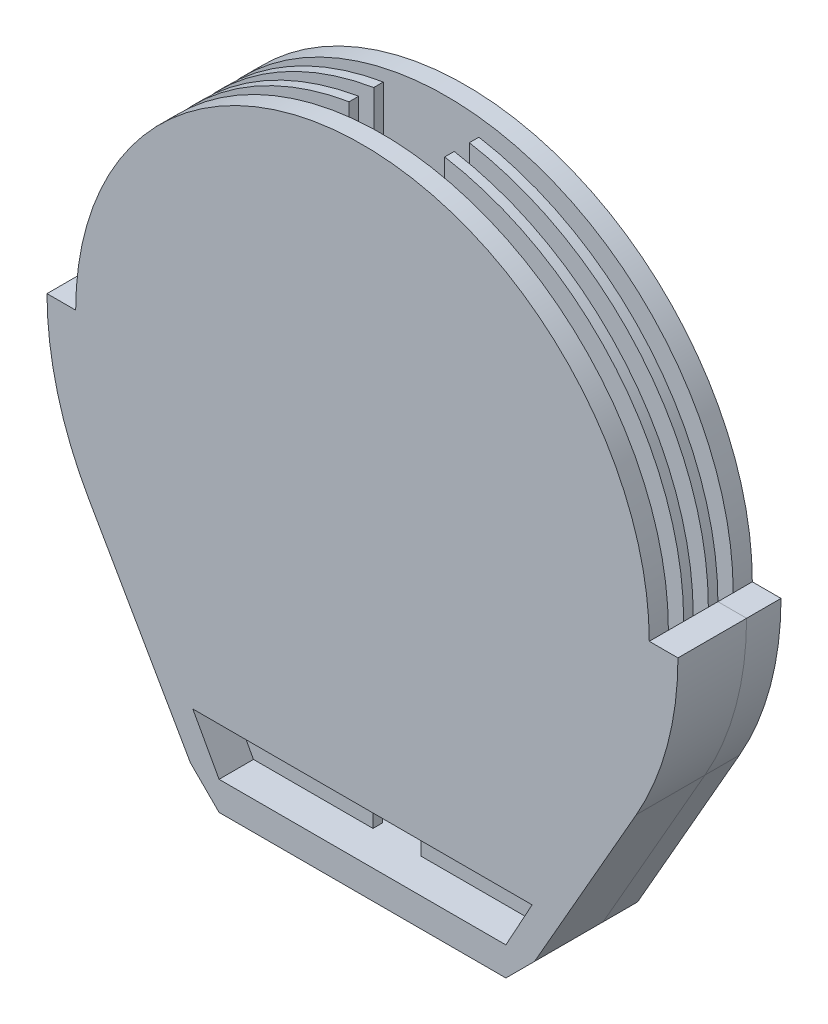
SolidWorks part; units mm, degrees
ref_plane "Plano frontal" through (0, 0, 0) normal (0, 0, 1) x (1, 0, 0)
ref_plane "Plano superior" through (0, 0, 0) normal (0, 1, 0) x (1, 0, 0)
ref_plane "Plano direito" through (0, 0, 0) normal (1, 0, 0) x (0, 0, -1)
sketch "Esboço1" plane through (0, 0, 0) normal (0, 0, 1) x (1, 0, 0)
  line L0 (5, -35) -> (15, -35)
  line L1 (-15, -35) -> (-5, -35)
  line L2 (15, -35) -> (26.2929, -14.4459)
  line L3 (-15, -35) -> (-26.2929, -14.4459)
  line L4 (-12, -30) -> (-5, -30)
  line L5 (-12, -30) -> (-21.889, -12.0777)
  line L6 (12, -30) -> (21.889, -12.0777)
  line L9 (5, -30) -> (12, -30)
  line L10 (-5, -30) -> (-2.5, -30)
  line L11 (-2.5, -32.5) -> (-2.5, -35)
  line L12 (-2.5, -35) -> (-5, -35)
  line L13 (2.5, -32.5) -> (2.5, -35)
  line L14 (2.5, -35) -> (5, -35)
  line L15 (-2.5, -32.5) -> (-2.5, -30)
  line L16 (2.5, -32.5) -> (2.5, -30)
  line L17 (2.5, -30) -> (5, -30)
  arc A0 (26.2929, -14.4459) -> (-26.2929, -14.4459) centre (0, 0) ccw
  arc A1 (21.889, -12.0777) -> (-21.889, -12.0777) centre (0, 0) ccw
  point P5 (0, -30)
  point P8 (0, -35)
  point P13 (0, -30)
  dimension "D1" = 60
  dimension "D2" = 50
  dimension "D8" = 2.5
  dimension "D3" = 30
  dimension "D4" = 24
  dimension "D5" = 10
  dimension "D6" = 5
  dimension "D7" = 5
extrude "Ressalto-extrusão3" add sketch "Esboço1" along normal blind 1
sketch "Esboço2" plane through (0, 0, 1) normal (0, 0, 1) x (1, 0, 0)
  line L0 (-30, 0) -> (-33, 0)
  line L1 (30, 0) -> (33, 0)
  line L2 (-15, -35) -> (-18, -35)
  line L3 (15, -35) -> (18, -35)
  line L4 (-18, -35) -> (-28.6469, -16.3816)
  line L5 (18, -35) -> (28.6469, -16.3816)
  line L6 (-15, -35) -> (-15, -38)
  line L7 (15, -35) -> (15, -38)
  line L8 (-15, -38) -> (15, -38)
  line L9 (18, -35) -> (15, -38)
  line L10 (-18, -35) -> (-15, -38)
  line L11 (-15, -35) -> (-26.2929, -14.4459)
  line L12 (15, -35) -> (26.2929, -14.4459)
  line L13 (-15, -35) -> (15, -35)
  arc A0 (26.2929, -14.4459) -> (-26.2929, -14.4459) centre (0, 0) ccw construction
  arc A1 (-33, 0) -> (-28.6469, -16.3816) centre (0, 0) ccw
  arc A2 (28.6469, -16.3816) -> (33, 0) centre (0, 0) ccw
  arc A3 (26.2929, -14.4459) -> (30, 0) centre (0, 0) ccw
  arc A4 (-30, 0) -> (-26.2929, -14.4459) centre (0, 0) ccw
  line M15 (2.5, -35) -> (15, -35)
  line M16 (15, -35) -> (26.2929, -14.4459)
  arc M17 (26.2929, -14.4459) -> (-26.2929, -14.4459) centre (0, 0) ccw
  line M18 (-26.2929, -14.4459) -> (-15, -35)
  line M19 (-15, -35) -> (-2.5, -35)
  dimension "D1" = 3
  dimension "D3" = 3
  dimension "D4" = 3
  dimension "D5" = 3
  dimension "D6" = 3
extrude "Ressalto-extrusão4" add sketch "Esboço2" against normal blind 3.58 contours L13 L6 L8 L7 M19 M15 | L9 L3 L7 | L5 A2 L1 L3 M17 M16 | L2 L10 L6 | L0 A1 L4 L2 M18 M17
sketch "Esboço4" plane through (0, 0, -2.58) normal (0, 0, -1) x (-1, 0, 0)
  line L0 (-15, -35) -> (-2.5, -35)
  line L1 (15, -35) -> (26.2929, -14.4459)
  line L2 (-15, -35) -> (-26.2929, -14.4459)
  line L3 (-12, -30) -> (-21.889, -12.0777)
  line L4 (12, -30) -> (21.889, -12.0777)
  line L5 (-2.5, -30) -> (-12, -30)
  line L6 (-2.5, -30) -> (-2.5, -35)
  line L7 (2.5, -35) -> (2.5, -30)
  line L8 (2.5, -30) -> (12, -30)
  line L9 (2.5, -35) -> (15, -35)
  arc A0 (26.2929, -14.4459) -> (-26.2929, -14.4459) centre (0, 0) ccw
  arc A1 (21.889, -12.0777) -> (-21.889, -12.0777) centre (0, 0) ccw
extrude "Ressalto-extrusão5" add sketch "Esboço4" against normal blind 1
sketch "Esboço5" plane through (0, 0, 1) normal (0, 0, 1) x (1, 0, 0)
  line L0 (-15, -38) -> (-18, -35)
  line L1 (-18, -35) -> (-28.6469, -16.3816)
  line L2 (-15, -38) -> (15, -38)
  line L3 (15, -38) -> (18, -35)
  line L4 (18, -35) -> (28.6469, -16.3816)
  line L5 (0, -35) -> (12.5, -35)
  line L6 (-12.5, -35) -> (-15, -35)
  line L7 (-2.5, -35) -> (2.5, -35) construction
  line L8 (0, -35) -> (-12.5, -35)
  line L9 (-15, -35) -> (-26.2929, -14.4459)
  line L10 (12.5, -35) -> (15, -35)
  line L11 (15, -35) -> (26.2929, -14.4459)
  line L12 (-33, 0) -> (-30, 0)
  line L13 (33, 0) -> (30, 0)
  arc A0 (28.6469, -16.3816) -> (33, 0) centre (0, 0) ccw
  arc A1 (26.2929, -14.4459) -> (30, 0) centre (0, 0) ccw
  arc A2 (-33, 0) -> (-28.6469, -16.3816) centre (0, 0) ccw
  arc A3 (-30, 0) -> (-26.2929, -14.4459) centre (0, 0) ccw
  dimension "D1" = 12.5
  dimension "D2" = 12.5
extrude "Ressalto-extrusão6" add sketch "Esboço5" along normal blind 1.6
sketch "Esboço6" plane through (0, 0, -2.58) normal (0, 0, -1) x (-1, 0, 0)
  line L0 (-15, -38) -> (-18, -35)
  line L1 (-33, 0) -> (-30, 0)
  line L2 (-18, -35) -> (-28.6469, -16.3816)
  line L3 (18, -35) -> (15, -38)
  line L4 (15, -38) -> (-15, -38)
  line L5 (18, -35) -> (28.6469, -16.3816)
  line L6 (30, 0) -> (33, 0)
  line L7 (-15, -35) -> (-26.2929, -14.4459)
  line L8 (15, -35) -> (26.2929, -14.4459)
  line L9 (-15, -35) -> (15, -35)
  arc A1 (28.6469, -16.3816) -> (33, 0) centre (0, 0) ccw
  arc A2 (-30, 0) -> (-26.2929, -14.4459) centre (0, 0) ccw
  arc A3 (26.2929, -14.4459) -> (30, 0) centre (0, 0) ccw
  arc A4 (-33, 0) -> (-28.6469, -16.3816) centre (0, 0) ccw
  arc A5 (28.6469, -16.3816) -> (33, 0) centre (0, 0) ccw
extrude "Ressalto-extrusão7" add sketch "Esboço6" along normal blind 1.6 separate body
sketch "Esboço8" plane through (0, 0, 2.6) normal (0, 0, 1) x (1, 0, 0)
  line L0 (-12, -30) -> (17.7471, -30)
  line L1 (26.2929, -14.4459) -> (15, -35) construction
  line L2 (-12, -30) -> (-17.7471, -30)
  line L3 (-15, -35) -> (-26.2929, -14.4459) construction
  line L4 (-17.7471, -30) -> (-15, -35)
  line L5 (-15, -35) -> (15, -35)
  line L6 (15, -35) -> (17.7471, -30)
  line L7 (-15, -38) -> (15, -38)
  line L8 (15, -38) -> (18, -35)
  line L9 (18, -35) -> (28.6469, -16.3816)
  line L10 (-15, -38) -> (-18, -35)
  line L11 (-18, -35) -> (-28.6469, -16.3816)
  line L12 (-33, 0) -> (-30, 0)
  line L13 (30, 0) -> (33, 0)
  arc A0 (28.6469, -16.3816) -> (33, 0) centre (0, 0) ccw
  arc A1 (30, 0) -> (-30, 0) centre (0, 0) ccw
  arc A3 (-33, 0) -> (-28.6469, -16.3816) centre (0, 0) ccw
sketch "Esboço9" plane through (0, 0, 1) normal (0, 0, 1) x (1, 0, 0)
  line L1 (-5, 36.4289) -> (5, 36.4289)
  line L2 (-5, 36.4289) -> (-5, 23.5711)
  line L3 (-5, 23.5711) -> (5, 23.5711)
  line L4 (5, 36.4289) -> (5, 23.5711)
  line L5 (-5, 36.4289) -> (5, 23.5711) construction
  line L6 (-5, 23.5711) -> (5, 36.4289) construction
  arc A0 (30, 0) -> (-30, 0) centre (0, 0) ccw construction
  point P0 (0, 30)
  dimension "D1" = 10
extrude "Corte-extrusão2" cut sketch "Esboço9" against normal blind 4
extrude "Ressalto-extrusão8" add sketch "Esboço8" along normal blind 2
sketch "Esboço11" plane through (0, 0, -4.18) normal (0, 0, -1) x (-1, 0, 0)
  line L0 (-15, -38) -> (15, -38)
  line L1 (15, -38) -> (18, -35)
  line L2 (-15, -38) -> (-18, -35)
  line L3 (-18, -35) -> (-28.6469, -16.3816)
  line L4 (18, -35) -> (28.6469, -16.3816)
  line L5 (-15, -35) -> (15, -35)
  line L6 (15, -35) -> (17.7471, -30)
  line L7 (-15, -35) -> (-17.7471, -30)
  line L8 (-12, -30) -> (17.7471, -30)
  line L9 (-17.7471, -30) -> (17.7471, -30) construction
  line L10 (-12, -30) -> (-17.7471, -30)
  line L11 (-30, 0) -> (-33, 0)
  line L12 (33, 0) -> (30, 0)
  arc A0 (28.6469, -16.3816) -> (33, 0) centre (0, 0) ccw
  arc A1 (30, 0) -> (-30, 0) centre (0, 0) ccw
  arc A2 (-33, 0) -> (-28.6469, -16.3816) centre (0, 0) ccw
extrude "Ressalto-extrusão9" add sketch "Esboço11" along normal blind 2
